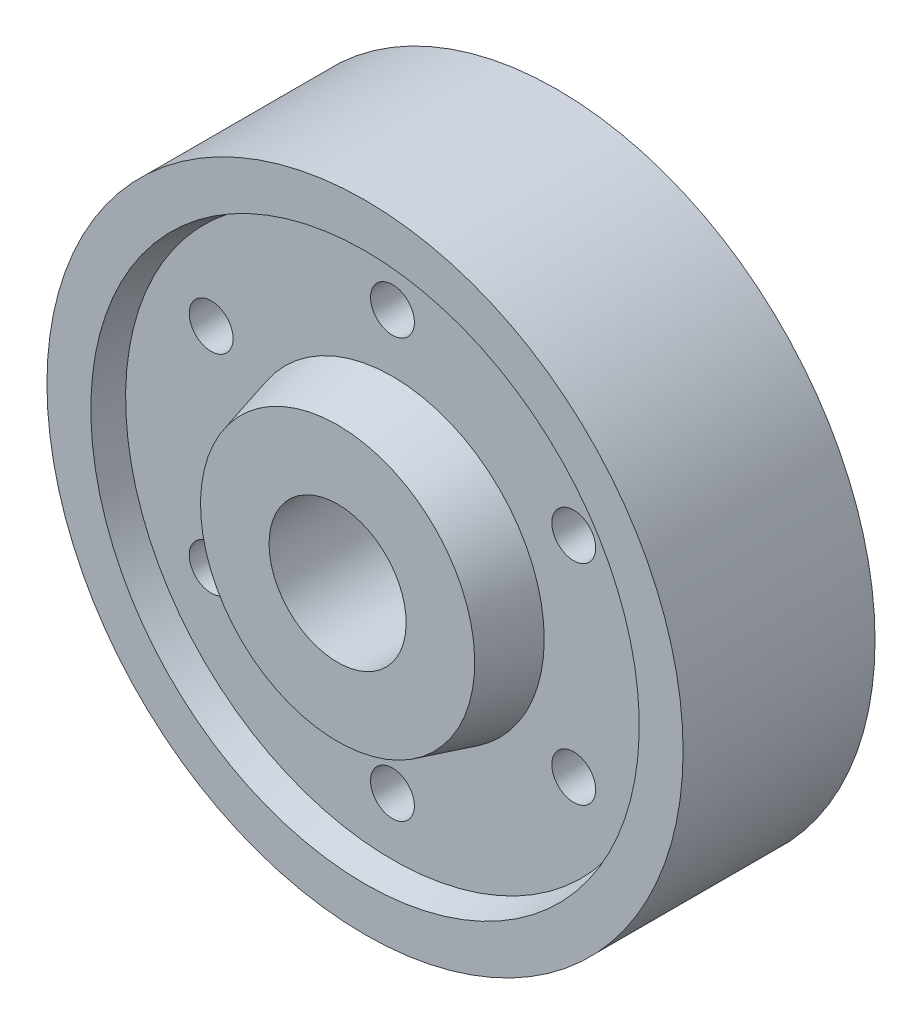
SolidWorks part; units mm, degrees
ref_plane "Front Plane" through (0, 0, 0) normal (0, 0, 1) x (1, 0, 0)
ref_plane "Top Plane" through (0, 0, 0) normal (0, 1, 0) x (1, 0, 0)
ref_plane "Right Plane" through (0, 0, 0) normal (1, 0, 0) x (0, 0, -1)
sketch "Sketch1" plane through (0, 0, 0) normal (1, 0, 0) x (0, 0, -1)
  line L1 (-45, 12.5) -> (-45, 25)
  line L6 (-40, 58) -> (-5, 58)
  line L11 (0, 25) -> (0, 12.5)
  line L12 (-45, 12.5) -> (0, 12.5)
  line L13 (0, 0) -> (-45, 0) construction
  line L14 (-45, 25) -> (-35, 27.6795)
  line L15 (-35, 27.6795) -> (-35, 48.6603)
  line L16 (-10, 48.6603) -> (-10, 27.6795)
  line L17 (-10, 27.6795) -> (0, 25)
  line L24 (-35, 48.6603) -> (-40, 50)
  line L25 (-40, 50) -> (-40, 58)
  line L26 (-5, 58) -> (-5, 50)
  line L27 (-5, 50) -> (-10, 48.6603)
  point P17 (-22.5, 58)
  point P18 (-22.5, 12.5)
  point P19 (-22.5, 0)
  dimension "D1" = 12.5
  dimension "D2" = 45
  dimension "D3" = 12.5
  dimension "D4" = 15
  dimension "D5" = 15
  dimension "D6" = 10
  dimension "D7" = 35
  dimension "D8" = 15
  dimension "D9" = 45
  dimension "D10" = 58
  dimension "D11" = 8
revolve "Revolve2" add sketch "Sketch1" angle 360 about L13
sketch "Sketch3" plane through (0, 0, 35) normal (0, 0, 1) x (1, 0, 0)
  line L0 (-55.8994, 0) -> (58, 0) construction
  line L1 (0, -64.713) -> (0, 60.287) construction
  line L2 (0, 48.6603) -> (0, 27.6795) construction
  circle A0 centre (0, 0) radius 58 construction
  circle A1 centre (0, 0) radius 48.6603 construction
  circle A2 centre (0, 0) radius 27.6795 construction
  circle A4 centre (0, 38.1699) radius 4
  circle A5 centre (33.0561, 19.0849) radius 4
  circle A6 centre (33.0561, -19.0849) radius 4
  circle A7 centre (0, -38.1699) radius 4
  circle A8 centre (-33.0561, -19.0849) radius 4
  circle A9 centre (-33.0561, 19.0849) radius 4
  point P29 (0, 0)
  dimension "D1" = 8
  dimension "D2" = 6
extrude "Cut-Extrude2" cut sketch "Sketch3" against normal blind 50 contours A8 | A4 | A9 | A7 | A6 | A5
